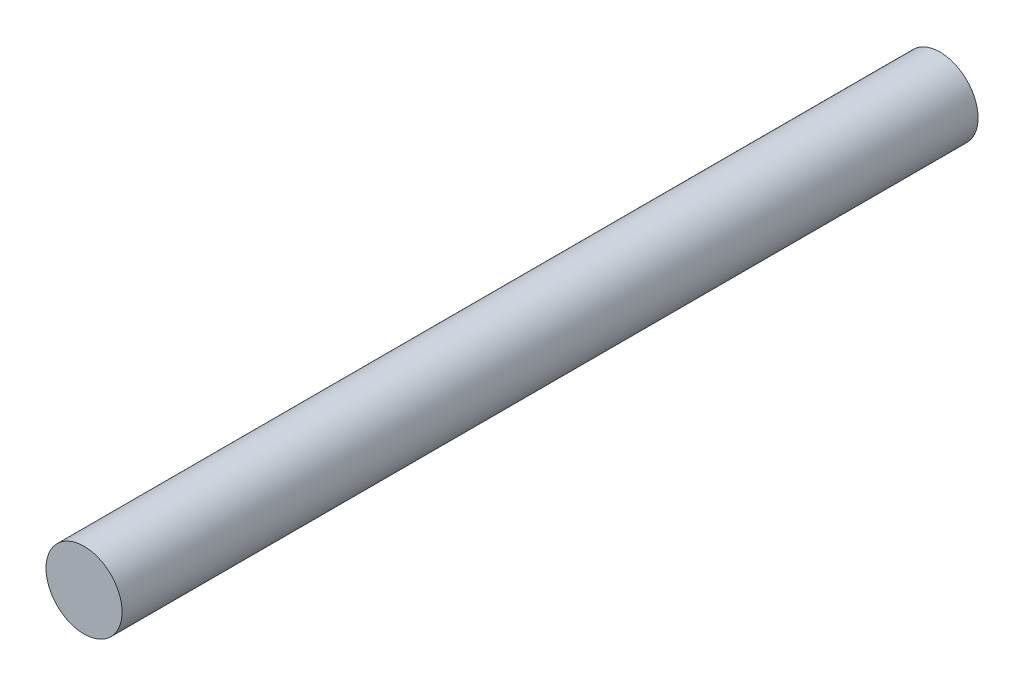
SolidWorks part; units mm, degrees
ref_plane "Front" through (0, 0, 0) normal (0, 0, 1) x (1, 0, 0)
ref_plane "Top" through (0, 0, 0) normal (0, 1, 0) x (1, 0, 0)
ref_plane "Right" through (0, 0, 0) normal (1, 0, 0) x (0, 0, -1)
sketch "Sketch1" plane through (0, 0, 0) normal (0, 0, 1) x (1, 0, 0)
  circle A0 centre (0, 0) radius 2
  dimension "D1" = 4
extrude "Boss-Extrude1" add sketch "Sketch1" along normal blind 45
